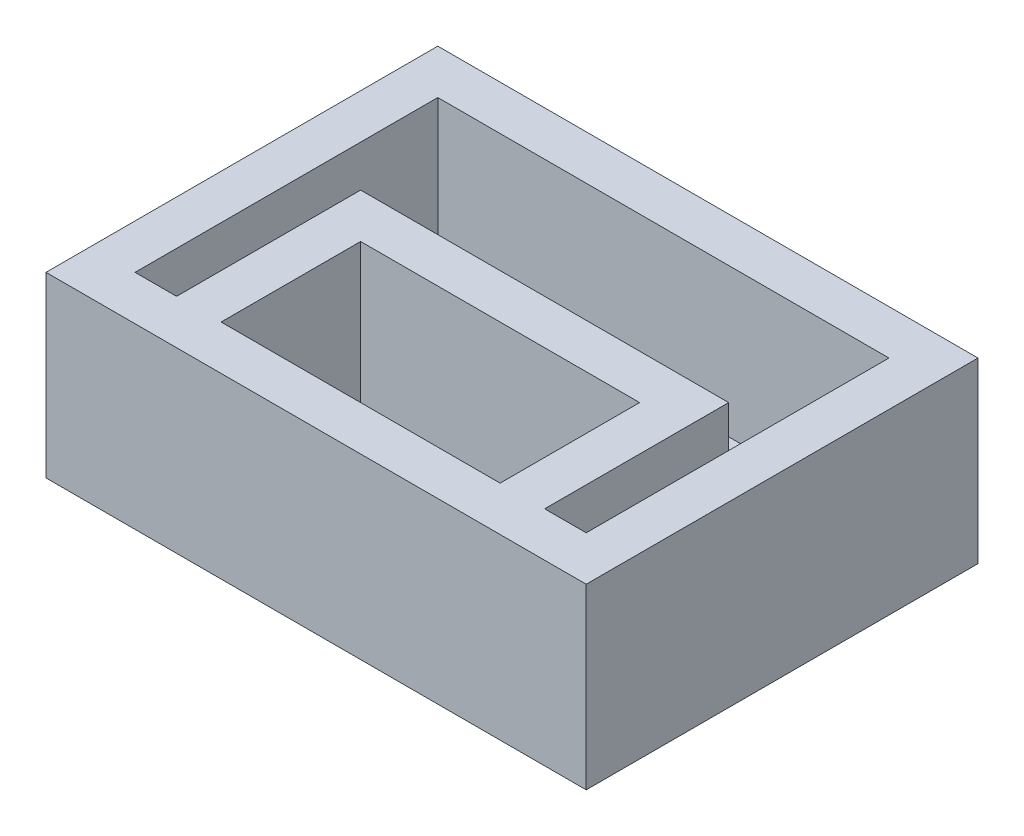
SolidWorks part; units mm, degrees
ref_plane "Front" through (0, 0, 0) normal (0, 0, 1) x (1, 0, 0)
ref_plane "Top" through (0, 0, 0) normal (0, 1, 0) x (1, 0, 0)
ref_plane "Right" through (0, 0, 0) normal (1, 0, 0) x (0, 0, -1)
sketch "Эскиз1" plane through (0, 0, 0) normal (0, 1, 0) x (1, 0, 0)
  line L0 (-6.2, -5.1) -> (-6.2, 1.1)
  line L1 (-7.6, 5.1) -> (7.6, 5.1)
  line L2 (-7.6, 5.1) -> (-7.6, -5.1)
  line L7 (-7.6, -5.1) -> (-6.2, -5.1)
  line L8 (7.6, 5.1) -> (7.6, -5.1)
  line L13 (0, -5.1) -> (0, 5.1) construction
  line L14 (-7.6, 0) -> (7.6, 0) construction
  line L19 (-9.1, 6.6) -> (9.1, 6.6)
  line L20 (-9.1, 6.6) -> (-9.1, -6.6)
  line L21 (-9.1, -6.6) -> (9.1, -6.6)
  line L22 (9.1, 6.6) -> (9.1, -6.6)
  line L23 (0, -6.6) -> (0, 6.6) construction
  line L30 (-9.1, 0) -> (9.1, 0) construction
  line L31 (-6.2, 1.1) -> (6.2, 1.1)
  line L32 (6.2, 1.1) -> (6.2, -5.1)
  line L35 (4.7, -5.1) -> (4.7, -0.4)
  line L36 (4.7, -0.4) -> (-4.7, -0.4)
  line L37 (-4.7, -0.4) -> (-4.7, -5.1)
  line L44 (-4.7, -5.1) -> (4.7, -5.1)
  line L45 (6.2, -5.1) -> (7.6, -5.1)
  point P0 (0, 0)
  point P4 (0, 0)
  dimension "D1" = 15.2
  dimension "D2" = 10.2
  dimension "D3" = 1.5
  dimension "D4" = 1.5
  dimension "D5" = 1.5
  dimension "D6" = 1.5
  dimension "D7" = 1.5
  dimension "D8" = 1.4
  dimension "D9" = 1.4
  dimension "D10" = 4
extrude "Бобышка-Вытянуть1" add sketch "Эскиз1" along normal blind 5
sketch "Эскиз6" plane through (0, 0, 0) normal (0, -1, 0) x (1, 0, 0)
  line L1 (-9.1, 6.6) -> (9.1, 6.6)
  line L2 (-9.1, 6.6) -> (-9.1, -6.6)
  line L3 (-9.1, -6.6) -> (9.1, -6.6)
  line L4 (9.1, 6.6) -> (9.1, -6.6)
extrude "Бобышка-Вытянуть4" add sketch "Эскиз6" along normal blind 1
sketch "Эскиз7" plane through (0, 0, 0) normal (0, 1, 0) x (1, 0, 0)
  line L0 (7.6, 5.1) -> (-7.6, 5.1) construction
  line L1 (-7.6, -5.1) -> (-6.2, -5.1)
  line L2 (-7.6, -5.1) -> (-7.6, 5.1)
  line L3 (-7.6, 5.1) -> (-6.2, 5.1)
  line L4 (-6.2, -5.1) -> (-6.2, 5.1)
  line L6 (7.6, 5.1) -> (6.2, 5.1)
  line L7 (7.6, 5.1) -> (7.6, -5.1)
  line L8 (7.6, -5.1) -> (6.2, -5.1)
  line L9 (6.2, 5.1) -> (6.2, -5.1)
extrude "Бобышка-Вытянуть5" add sketch "Эскиз7" along normal blind 1
